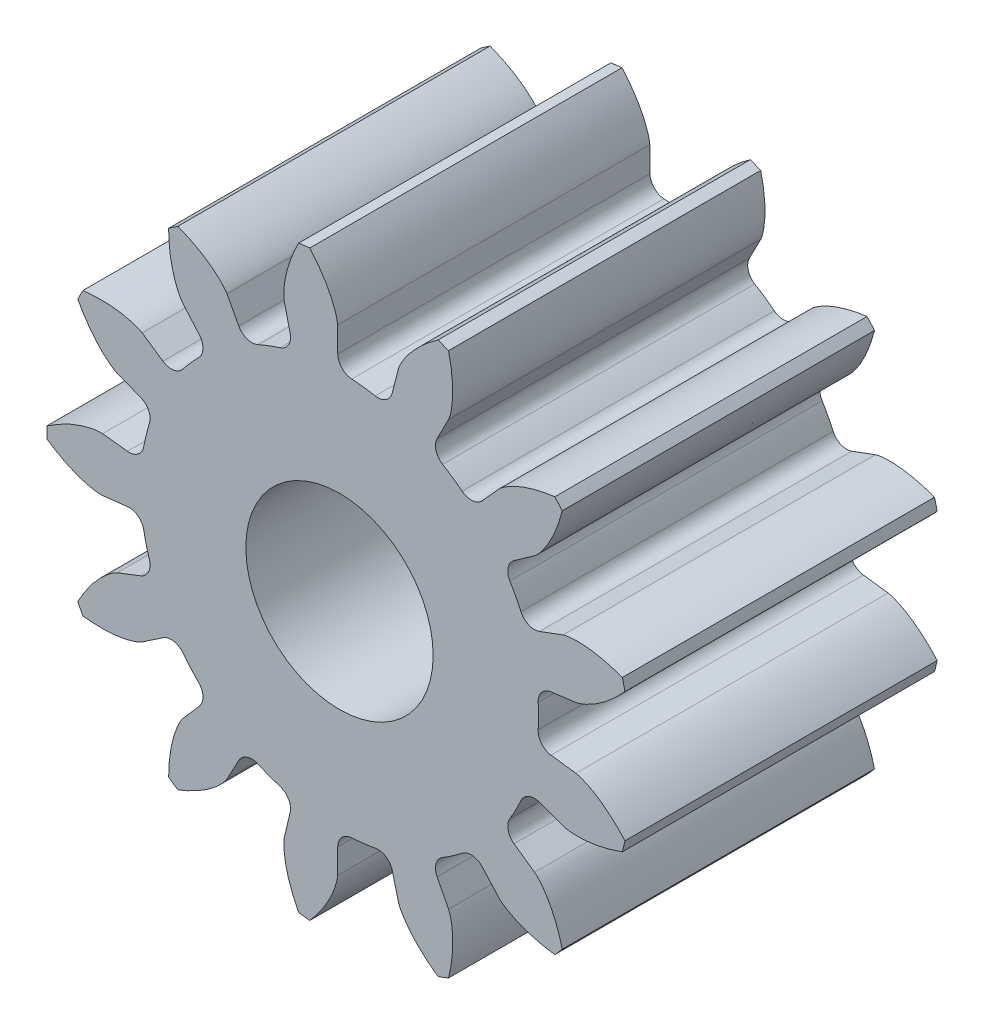
SolidWorks part; units mm, degrees
ref_plane "Front Plane" through (0, 0, 0) normal (0, 0, 1) x (1, 0, 0)
ref_plane "Top Plane" through (0, 0, 0) normal (0, 1, 0) x (1, 0, 0)
ref_plane "Right Plane" through (0, 0, 0) normal (1, 0, 0) x (0, 0, -1)
ref_axis "Gear Axis" through (0, 0, -0.5001) along (0, 0, 1)
sketch "Blank Sketch" plane through (0, 0, 0) normal (0, 0, 1) x (1, 0, 0)
  circle A0 centre (0, 0) radius 9.375
  dimension "OD" = 18.75
extrude "Blank" add sketch "Blank Sketch" along normal blind 10
sketch "Tooth Space Sketch" plane through (0, 0, 0) normal (0, 0, 1) x (1, 0, 0)
  line L0 (7.5716, 0.9822) -> (6.7767, 0.8791)
  line L1 (7.5716, -0.9822) -> (6.7767, -0.8791)
  line L2 (10.0594, 3.4204) -> (10.0594, -3.4204)
  arc A0 (6.7767, 0.8791) -> (6.3637, 0.3798) centre (6.8378, 0.408) ccw
  arc A1 (6.3637, -0.3798) -> (6.7767, -0.8791) centre (6.8378, -0.408) ccw
  arc A2 (6.3637, -0.3798) -> (6.3637, 0.3798) centre (0, 0) ccw
  spline S0 degree 4 poles (7.5716, 0.9822) (7.5768, 0.983) (7.5914, 0.9855) (7.6188, 0.9916) (7.6631, 1.0034) (7.7189, 1.0211) (7.79, 1.0471) (7.8726, 1.0815) (7.9619, 1.1233) (8.0573, 1.173) (8.1507, 1.2264) (8.2424, 1.283) (8.3321, 1.3424) (8.4388, 1.4178) (8.564, 1.5131) (8.7061, 1.6314) (8.8619, 1.7734) (9.0147, 1.9263) (9.16, 2.0834) (9.3006, 2.2494) (9.4323, 2.4151) (9.5624, 2.5942) (9.6791, 2.7631) (9.802, 2.9597) (9.899, 3.1205) (10.0184, 3.34) (10.0864, 3.4718) (10.1629, 3.6284) (10.1952, 3.6992) (10.2152, 3.7428) knots 0 0 0 0 0 0.005377 0.015084 0.028532 0.04661 0.064855 0.092111 0.119476 0.146842 0.174209 0.201575 0.228941 0.256307 0.307035 0.361767 0.4165 0.471232 0.525964 0.580697 0.635429 0.690161 0.744894 0.799626 0.854358 0.909091 0.954545 1 1 1 1 1 construction
  spline S1 degree 4 poles (7.5716, 0.9822) (7.5768, 0.983) (7.5914, 0.9855) (7.6188, 0.9916) (7.6631, 1.0034) (7.7189, 1.0211) (7.79, 1.0471) (7.8726, 1.0815) (7.9619, 1.1233) (8.0573, 1.173) (8.1507, 1.2264) (8.2424, 1.283) (8.3321, 1.3424) (8.4388, 1.4178) (8.564, 1.5131) (8.7061, 1.6314) (8.8619, 1.7734) (9.0147, 1.9263) (9.16, 2.0834) (9.3006, 2.2494) (9.4323, 2.4151) (9.5624, 2.5942) (9.6791, 2.7631) (9.802, 2.9597) (9.899, 3.1205) (9.9925, 3.2924) (10.0371, 3.3769) (10.0594, 3.4204) knots 0 0 0 0 0 0.005377 0.015084 0.028532 0.04661 0.064855 0.092111 0.119476 0.146842 0.174209 0.201575 0.228941 0.256307 0.307035 0.361767 0.4165 0.471232 0.525964 0.580697 0.635429 0.690161 0.744894 0.799626 0.854358 0.909091 0.909091 0.909091 0.909091 0.909091
  spline S2 degree 4 poles (7.5716, -0.9822) (7.5768, -0.983) (7.5914, -0.9855) (7.6188, -0.9916) (7.6631, -1.0034) (7.7189, -1.0211) (7.79, -1.0471) (7.8726, -1.0815) (7.9619, -1.1233) (8.0573, -1.173) (8.1507, -1.2264) (8.2424, -1.283) (8.3321, -1.3424) (8.4388, -1.4178) (8.564, -1.5131) (8.7061, -1.6314) (8.8619, -1.7734) (9.0147, -1.9263) (9.16, -2.0834) (9.3006, -2.2494) (9.4323, -2.4151) (9.5624, -2.5942) (9.6791, -2.7631) (9.802, -2.9597) (9.899, -3.1205) (10.0184, -3.34) (10.0864, -3.4718) (10.1629, -3.6284) (10.1952, -3.6992) (10.2152, -3.7428) knots 0 0 0 0 0 0.005377 0.015084 0.028532 0.04661 0.064855 0.092111 0.119476 0.146842 0.174209 0.201575 0.228941 0.256307 0.307035 0.361767 0.4165 0.471232 0.525964 0.580697 0.635429 0.690161 0.744894 0.799626 0.854358 0.909091 0.954545 1 1 1 1 1 construction
  spline S3 degree 4 poles (7.5716, -0.9822) (7.5768, -0.983) (7.5914, -0.9855) (7.6188, -0.9916) (7.6631, -1.0034) (7.7189, -1.0211) (7.79, -1.0471) (7.8726, -1.0815) (7.9619, -1.1233) (8.0573, -1.173) (8.1507, -1.2264) (8.2424, -1.283) (8.3321, -1.3424) (8.4388, -1.4178) (8.564, -1.5131) (8.7061, -1.6314) (8.8619, -1.7734) (9.0147, -1.9263) (9.16, -2.0834) (9.3006, -2.2494) (9.4323, -2.4151) (9.5624, -2.5942) (9.6791, -2.7631) (9.802, -2.9597) (9.899, -3.1205) (9.9925, -3.2924) (10.0371, -3.3769) (10.0594, -3.4204) knots 0 0 0 0 0 0.005377 0.015084 0.028532 0.04661 0.064855 0.092111 0.119476 0.146842 0.174209 0.201575 0.228941 0.256307 0.307035 0.361767 0.4165 0.471232 0.525964 0.580697 0.635429 0.690161 0.744894 0.799626 0.854358 0.909091 0.909091 0.909091 0.909091 0.909091
  dimension "Root" = 6.375
  dimension "Fillet" = 0.475
extrude "Tooth Space" cut sketch "Tooth Space Sketch" against normal through all both and the other way through all both
pattern_circular "Teeth" count 13 over 360 about axis through (0, 0, -0.5001) along (0, 0, 1) of "Tooth Space"
sketch "Sketch1" plane through (0, 0, 0) normal (0, 0, -1) x (-1, 0, 0)
  circle A0 centre (0, 0) radius 3
  dimension "D1" = 6
extrude "Cut-Extrude1" cut sketch "Sketch1" against normal blind 10
equation "\"No. of Teeth\"= 13"
equation "\"Module\"= 1.25"
equation "\"Bore Diameter\"= 0"
equation "\"Pressure Angle\"= 20"
equation "\"Outer Diameter\"= ( \"No. of Teeth\" + 2 ) * \"Module\""
equation "\"Pitch Diameter\"= \"No. of Teeth\" * \"Module\""
equation "\"Backlash\"= 0.3 * \"Module\""
equation "\"Arc Length\"= ( ( \"Module\" * pi ) / 2 + \"Backlash\" )"
equation "\"Fillet Radius\"= 0.38 * \"Module\""
equation "\"Tooth Depth\"= IIF ( \"Module\" <= 1.25 , \"Module\" * 2.4 , \"Module\" * 2.25 )"
equation "\"Face Width\"= 10"
equation "\"Root Diameter\"= \"Outer Diameter\" - 2 * \"Tooth Depth\""
equation "\"Base Diameter\"= \"Pitch Diameter\" * cos ( \"Pressure Angle\" )"
equation "\"Base Radius\"= \"Base Diameter\" / 2"
equation "\"Tooth Thickness\"= \"Module\" * pi - \"Arc Length\""
equation "\"Half Space Angle\"= ( \"Arc Length\" / \"Pitch Diameter\" ) * 180 / pi"
equation "\"Involute Fn\"= tan ( \"Pressure Angle\" ) - \"Pressure Angle\" * pi / 180"
equation "\"Flank Offset\"= \"Arc Length\" / \"Pitch Diameter\" - \"Involute Fn\""
equation "\"Tip Cap Diameter\"= \"Outer Diameter\" + 2 * \"Module\""
equation "\"Flank Start Diameter\"= IIF ( \"Base Diameter\" >= ( \"Root Diameter\" + 3 * \"Fillet Radius\" ) , \"Base Diameter\" , \"Root Diameter\" + 3 * \"Fillet Radius\" )"
equation "\"Involute t1\"= ( abs ( ( \"Flank Start Diameter\" / \"Base Diameter\" ) ^ 2 - 1 ) ) ^ 0.5"
equation "\"Involute t2\"= ( abs ( ( \"Tip Cap Diameter\" / \"Base Diameter\" ) ^ 2 - 1 ) ) ^ 0.5"
equation "\"Flank Arc Radius\"= ( \"Pitch Diameter\" / 2 ) * sin ( \"Pressure Angle\" )"
equation "\"Flank Centre Angle\"= \"Half Space Angle\" + \"Pressure Angle\""
equation "\"OD@Blank Sketch\"= \"Outer Diameter\""
equation "\"Width@Blank\"= \"Face Width\""
equation "\"Root@Tooth Space Sketch\"= \"Root Diameter\" / 2"
equation "\"Fillet@Tooth Space Sketch\"= \"Fillet Radius\""
equation "\"Count@Teeth\"= \"No. of Teeth\""
